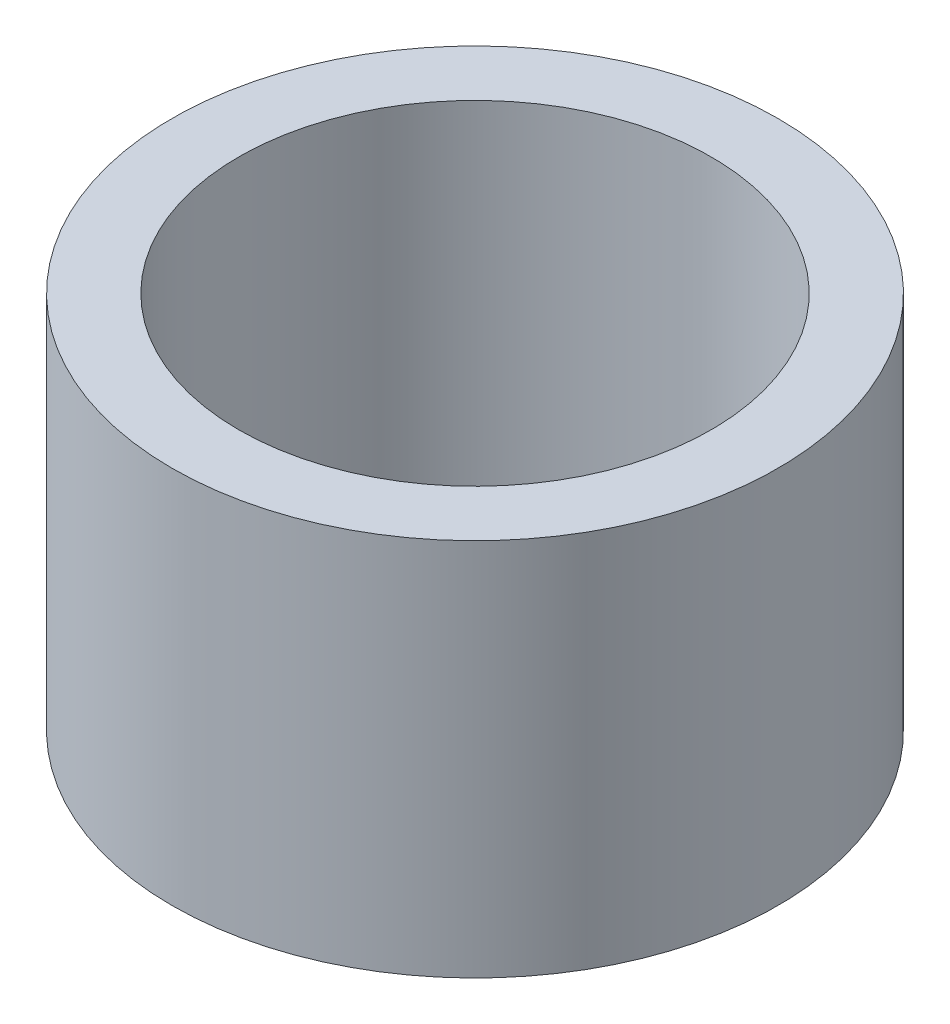
SolidWorks part; units mm, degrees
ref_plane "Front Plane" through (0, 0, 0) normal (0, 0, 1) x (1, 0, 0)
ref_plane "Top Plane" through (0, 0, 0) normal (0, 1, 0) x (1, 0, 0)
ref_plane "Right Plane" through (0, 0, 0) normal (1, 0, 0) x (0, 0, -1)
sketch "Sketch1" plane through (0, 0, 0) normal (0, 1, 0) x (1, 0, 0)
  circle A0 centre (0, 0) radius 15.6
  circle A1 centre (0, 0) radius 20
  dimension "D1" = 31.2
  dimension "D2" = 40
extrude "Boss-Extrude1" add sketch "Sketch1" along normal blind 25
